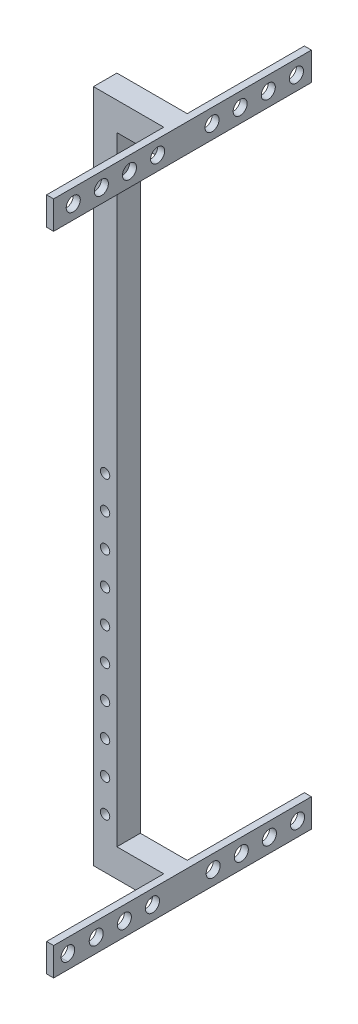
SolidWorks part; units mm, degrees
material "Custom Plastic"
ref_plane "Front Plane" through (0, 0, 0) normal (0, 0, 1) x (1, 0, 0)
ref_plane "Top Plane" through (0, 0, 0) normal (0, 1, 0) x (1, 0, 0)
ref_plane "Right Plane" through (0, 0, 0) normal (1, 0, 0) x (0, 0, -1)
sketch "Sketch1" plane through (0, 0, 0) normal (0, 1, 0) x (1, 0, 0)
  line L1 (-81.3492, 10.5159) -> (-31.3492, 10.5159)
  line L2 (-81.3492, 10.5159) -> (-81.3492, -39.4841)
  line L3 (-81.3492, -39.4841) -> (-31.3492, -39.4841)
  line L4 (-31.3492, 10.5159) -> (-31.3492, -39.4841)
  dimension "D1" = 50
  dimension "D2" = 50
extrude "Boss-Extrude1" add sketch "Sketch1" along normal blind 1439.7
sketch "Sketch2" plane through (-31.3492, 0, 0) normal (1, 0, 0) x (0, 0, -1)
  line L0 (10.5159, 1439.7) -> (10.5159, 0) construction
  line L1 (-39.4841, 1439.7) -> (10.5159, 1439.7)
  line L2 (-39.4841, 1439.7) -> (-39.4841, 1379.7)
  line L3 (-39.4841, 1379.7) -> (10.5159, 1379.7)
  line L4 (10.5159, 1439.7) -> (10.5159, 1379.7)
  line L6 (-39.4841, 0) -> (10.5159, 0)
  line L7 (-39.4841, 0) -> (-39.4841, 60)
  line L8 (-39.4841, 60) -> (10.5159, 60)
  line L9 (10.5159, 0) -> (10.5159, 60)
  dimension "D1" = 60
  dimension "D2" = 60
extrude "Boss-Extrude2" add sketch "Sketch2" along normal blind 100
sketch "Sketch3" plane through (68.6508, 0, 0) normal (1, 0, 0) x (0, 0, -1)
  line L1 (-39.4841, 1439.7) -> (260.5159, 1439.7)
  line L2 (-39.4841, 1439.7) -> (-39.4841, 1379.7)
  line L3 (-39.4841, 1379.7) -> (260.5159, 1379.7)
  line L4 (260.5159, 1439.7) -> (260.5159, 1379.7)
  line L5 (10.5159, 1379.7) -> (-289.4841, 1379.7)
  line L6 (10.5159, 1379.7) -> (10.5159, 1439.7)
  line L7 (10.5159, 1439.7) -> (-289.4841, 1439.7)
  line L8 (-289.4841, 1379.7) -> (-289.4841, 1439.7)
  line L9 (-39.4841, 60) -> (260.5159, 60)
  line L10 (-39.4841, 60) -> (-39.4841, 0)
  line L11 (-39.4841, 0) -> (260.5159, 0)
  line L12 (260.5159, 60) -> (260.5159, 0)
  line L13 (10.5159, 0) -> (-289.4841, 0)
  line L14 (10.5159, 0) -> (10.5159, 60)
  line L15 (10.5159, 60) -> (-289.4841, 60)
  line L16 (-289.4841, 0) -> (-289.4841, 60)
  line M5 (-39.4841, 1439.7) -> (-39.4841, 1379.7)
  line M6 (-39.4841, 1379.7) -> (10.5159, 1379.7)
  line M7 (10.5159, 1379.7) -> (10.5159, 1439.7)
  line M8 (10.5159, 1439.7) -> (-39.4841, 1439.7)
  dimension "D1" = 300
  dimension "D2" = 300
  dimension "D3" = 300
  dimension "D4" = 300
extrude "Boss-Extrude3" add sketch "Sketch3" along normal blind 15 contours L16 L13 L10 L15 | L14 L11 L12 L9 | L8 L5 L7 M5 | L4 L1 L3 M7 | M8 M5 M6 M7 | L11 L14 L9 L10
sketch "Sketch4" plane through (0, 0, 39.4841) normal (0, 0, 1) x (1, 0, 0)
  line L0 (-56.5779, 107.4674) -> (-56.5779, 610.4745)
  circle A0 centre (-56.5779, 107.4674) radius 10
  circle A1 centre (-56.5779, 177.4674) radius 10
  circle A2 centre (-56.5779, 247.4674) radius 10
  circle A3 centre (-56.5779, 317.4674) radius 10
  circle A4 centre (-56.5779, 387.4674) radius 10
  circle A5 centre (-56.5779, 457.4674) radius 10
  circle A6 centre (-56.5779, 527.4674) radius 10
  circle A7 centre (-56.5779, 597.4674) radius 10
  circle A8 centre (-56.5779, 667.4674) radius 10
  circle A9 centre (-56.5779, 737.4674) radius 10
  dimension "D1" = 10
extrude "Cut-Extrude1" cut sketch "Sketch4" against normal through all
sketch "Sketch5" plane through (68.6508, 0, 0) normal (-1, 0, 0) x (0, 0, 1)
  circle A0 centre (-228.5395, 1409.7) radius 15
  circle A1 centre (-168.5395, 1409.7) radius 15
  circle A2 centre (-108.5395, 1409.7) radius 15
  circle A3 centre (-48.5395, 1409.7) radius 15
  circle A4 centre (247.6472, 1409.7) radius 15
  circle A5 centre (187.6472, 1409.7) radius 15
  circle A6 centre (127.6472, 1409.7) radius 15
  circle A7 centre (67.6472, 1409.7) radius 15
  dimension "D1" = 4
  dimension "D2" = 4
extrude "Cut-Extrude2" cut sketch "Sketch5" against normal through all
sketch "Sketch7" plane through (68.6508, 0, 0) normal (-1, 0, 0) x (0, 0, 1)
  circle A1 centre (-230.9172, 30) radius 15
  circle A2 centre (-170.9172, 30) radius 15
  circle A3 centre (-110.9172, 30) radius 15
  circle A4 centre (-50.9172, 30) radius 15
  arc A5 (259.1113, 44.9913) -> (259.1113, 15.0087) centre (259.6212, 30) ccw
  circle A6 centre (78.6015, 30) radius 15
  circle A7 centre (138.6015, 30) radius 15
  circle A8 centre (198.6015, 30) radius 15
  arc A9 (259.1113, 44.9913) -> (259.1113, 15.0087) centre (258.6015, 30) cw
  dimension "D1" = 4
extrude "Cut-Extrude3" cut sketch "Sketch7" against normal through all
